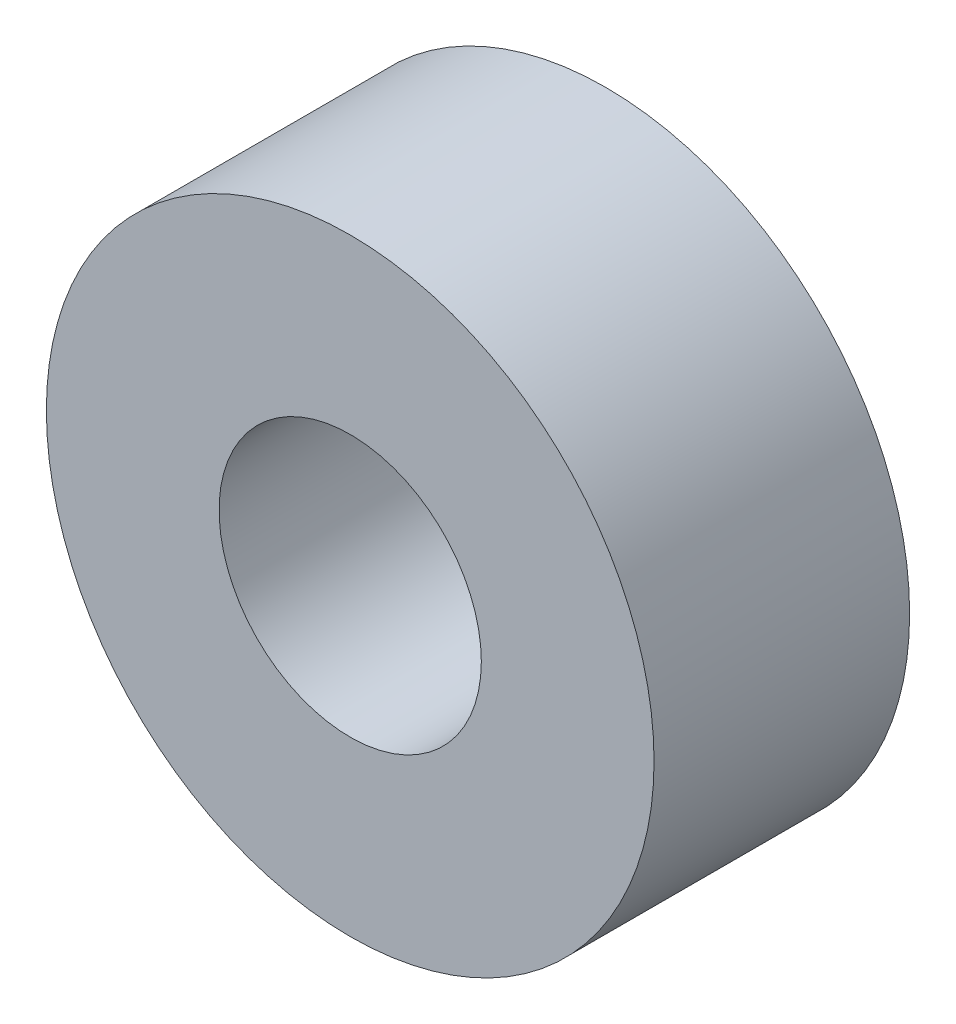
SolidWorks part; units mm, degrees
material "Cast Alloy Steel"
ref_plane "Front Plane" through (0, 0, 0) normal (0, 0, 1) x (1, 0, 0)
ref_plane "Top Plane" through (0, 0, 0) normal (0, 1, 0) x (1, 0, 0)
ref_plane "Right Plane" through (0, 0, 0) normal (1, 0, 0) x (0, 0, -1)
sketch "Sketch1" plane through (0, 0, 0) normal (0, 0, 1) x (1, 0, 0)
  circle A0 centre (0, 0) radius 41.61
extrude "Boss-Extrude1" add sketch "Sketch1" along normal blind 35
sketch "Sketch2" plane through (0, 0, 35) normal (0, 0, 1) x (1, 0, 0)
  circle A0 centre (0, 0) radius 17.9565
extrude "Cut-Extrude1" cut sketch "Sketch2" against normal blind 35
